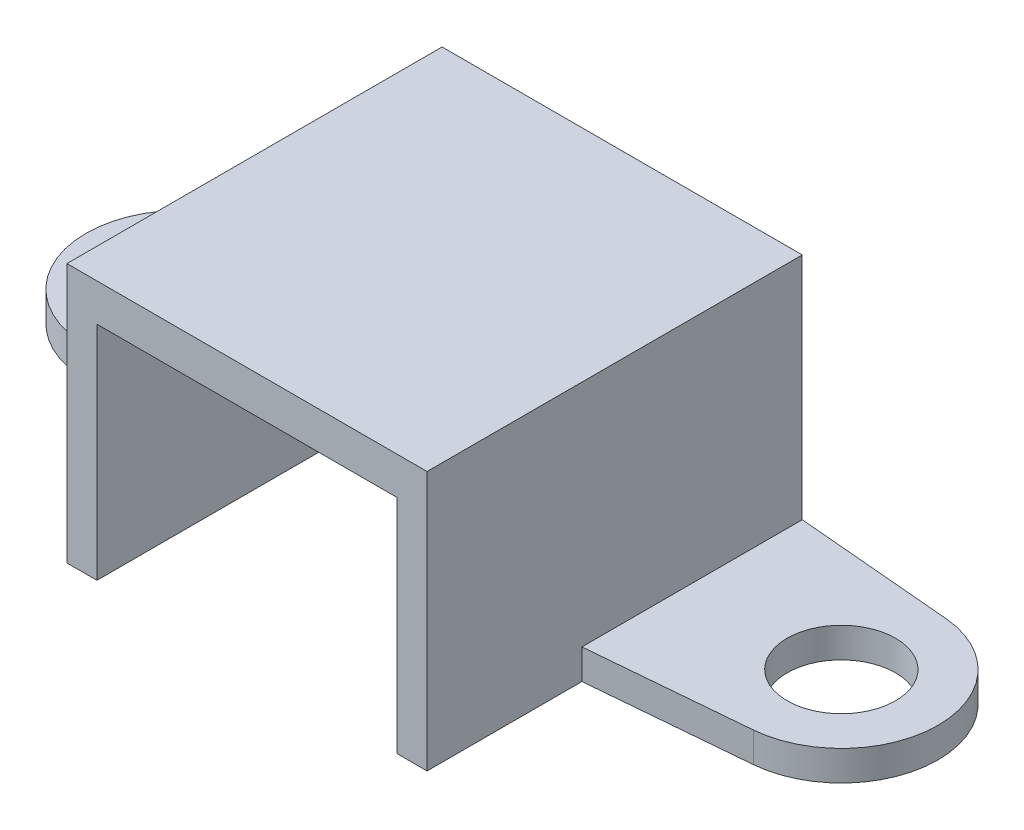
SolidWorks part; units mm, degrees
ref_plane "Alzado" through (0, 0, 0) normal (0, 0, 1) x (1, 0, 0)
ref_plane "Planta" through (0, 0, 0) normal (0, 1, 0) x (1, 0, 0)
ref_plane "Vista lateral" through (0, 0, 0) normal (1, 0, 0) x (0, 0, -1)
sketch "Croquis1" plane through (0, 0, 0) normal (0, 0, 1) x (1, 0, 0)
  line L0 (0, 0) -> (0, 10.3693)
  line L1 (0, 10.3693) -> (14.4, 10.3693)
  line L2 (14.4, 10.3693) -> (14.4, 0)
  line L3 (14.4, 0) -> (13.2, 0)
  line L4 (13.2, 0) -> (13.2, 8.8693)
  line L5 (13.2, 8.8693) -> (1.2, 8.8693)
  line L6 (1.2, 8.8693) -> (1.2, 0)
  line L7 (1.2, 0) -> (0, 0)
  point P3 (13.2, 4.4347)
  dimension "D1" = 1.2
  dimension "D2" = 1.2
  dimension "D3" = 1.5
  dimension "D4" = 12
extrude "Saliente-Extruir1" add sketch "Croquis1" against normal blind 15
sketch "Croquis2" plane through (0, 0, 0) normal (0, -1, 0) x (1, 0, 0)
  line L0 (-3.8, -10.5955) -> (1.2, -10.5955) construction
  line L1 (1.2, -15) -> (1.2, 0) construction
  line L2 (0, -15) -> (-6.3047, -14.4484)
  line L3 (0, -15) -> (-1.6947, -15)
  line L4 (0, -6.1911) -> (-6.3047, -6.7426)
  line L5 (0, -6.1911) -> (0, -15)
  line L6 (7.2, -15) -> (7.2, -10.9876) construction
  line L7 (1.2, -15) -> (13.2, -15) construction
  line L8 (14.4, -6.1911) -> (14.4, -15)
  line L9 (14.4, -15) -> (20.7047, -14.4484)
  line L10 (14.4, -6.1911) -> (20.7047, -6.7426)
  circle A0 centre (-5.9676, -10.5955) radius 2.1676
  arc A2 (-6.3047, -6.7426) -> (-6.3047, -14.4484) centre (-5.9676, -10.5955) ccw
  circle A3 centre (-5.9676, -10.5955) radius 3.8676 construction
  arc A4 (20.7047, -6.7426) -> (20.7047, -14.4484) centre (20.3676, -10.5955) cw
  circle A5 centre (20.3676, -10.5955) radius 2.1676
  line M16 (0, 0) -> (0, -15)
  dimension "D1" = 5
  dimension "D3" = 5
  dimension "D2" = 1.7
extrude "Saliente-Extruir2" add sketch "Croquis2" against normal blind 1.2 contours A4 L10 L8 L9 A5 | L4 A2 L2 A0 M16
